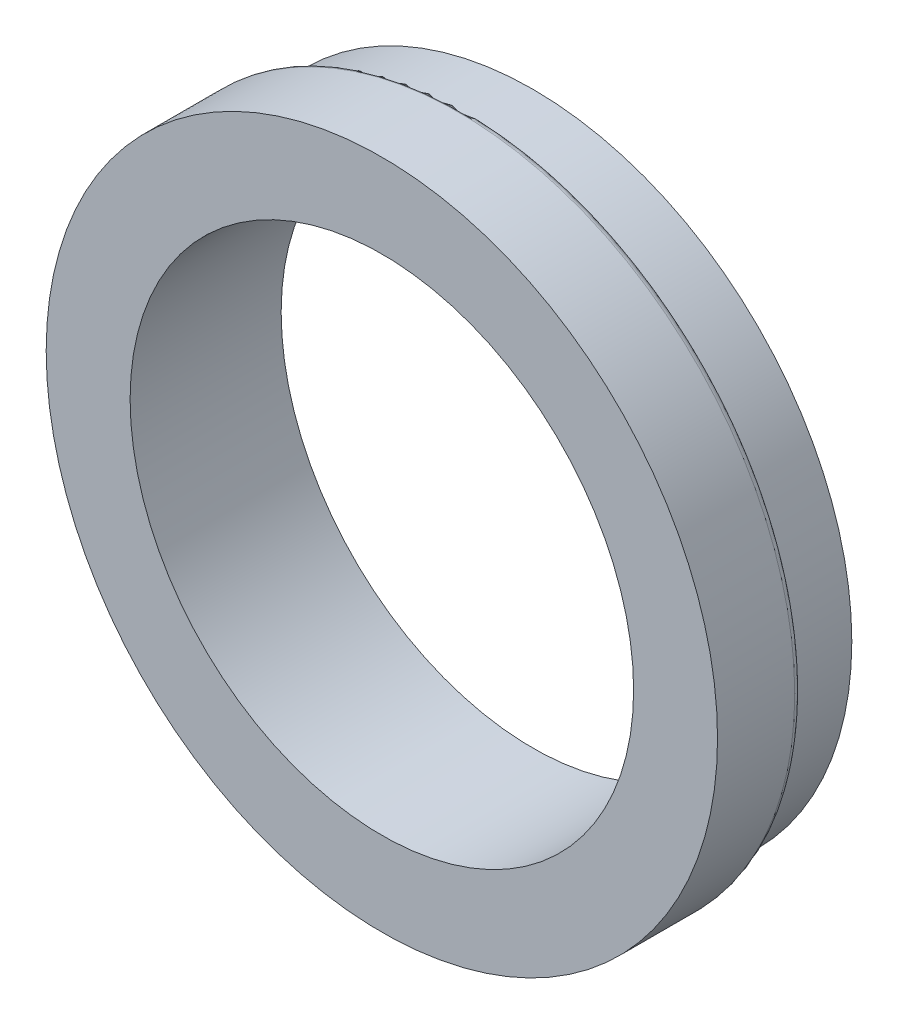
SolidWorks part; units mm, degrees
material "AISI 4340 Stahllegierung"
ref_plane "Ebene vorne" through (0, 0, 0) normal (0, 0, 1) x (1, 0, 0)
ref_plane "Ebene oben" through (0, 0, 0) normal (0, 1, 0) x (1, 0, 0)
ref_plane "Ebene rechts" through (0, 0, 0) normal (1, 0, 0) x (0, 0, -1)
sketch "Skizze2" plane through (0, 0, 0) normal (0, 0, 1) x (1, 0, 0)
  circle A0 centre (0, 0) radius 75
  circle A1 centre (0, 0) radius 95
  dimension "D1" = 150
  dimension "D2" = 20
extrude "Aufsatz-Linear austragen1" add sketch "Skizze2" along normal blind 20
ref_axis "Achse1" through (0, 0, 20) along (0, 0, -1)
sketch "Skizze3" plane through (0, 0, 0) normal (0, 1, 0) x (1, 0, 0)
  line L0 (100, -20) -> (100, -45)
  line L1 (100, -45) -> (75, -45)
  line L2 (75, -45) -> (75, -20)
  line L3 (-95, -20) -> (95, -20) construction
  line L4 (75, -20) -> (100, -20)
  line L5 (95, -20) -> (95, 0) construction
  dimension "D1" = 25
  dimension "D2" = 25
  dimension "D3" = 5
revolve "Rotation1" add sketch "Skizze3" angle 360 about axis through (0, 0, 20) along (0, 0, -1)
fillet "Verrundung3" radius 2 2 edges at (95, 0, 20) (100, 0, 20)
